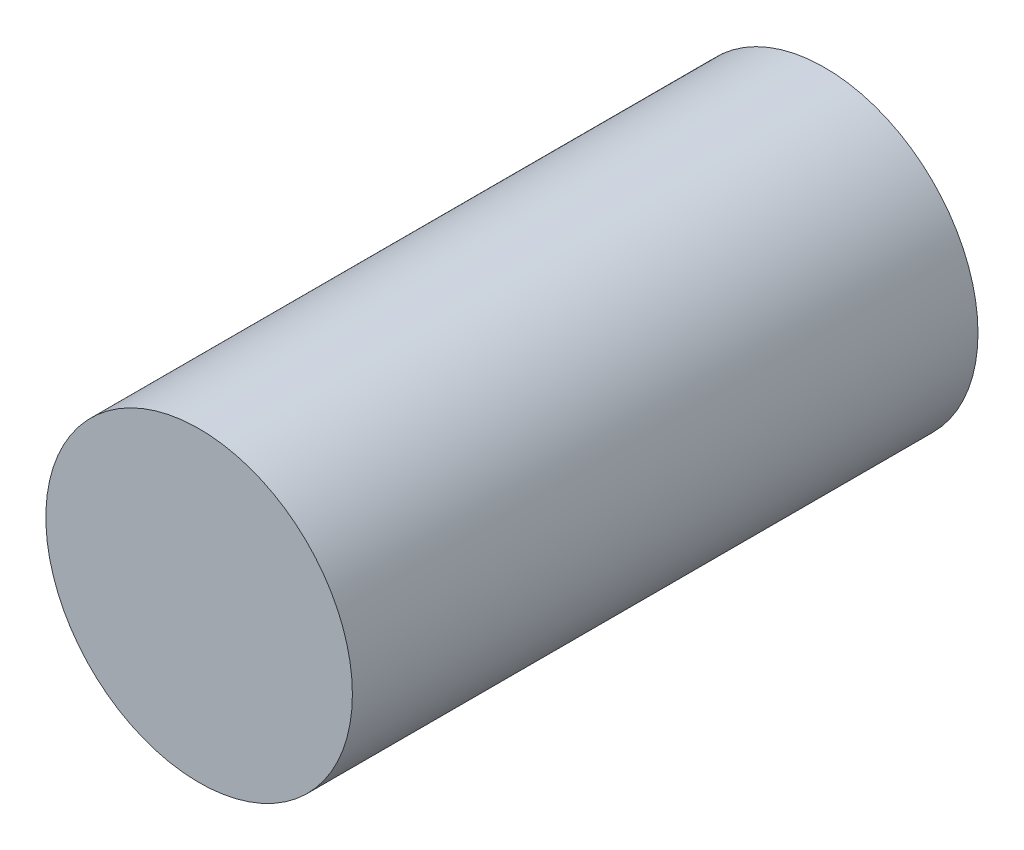
SolidWorks part; units mm, degrees
ref_plane "前视基准面" through (0, 0, 0) normal (0, 0, 1) x (1, 0, 0)
ref_plane "上视基准面" through (0, 0, 0) normal (0, 1, 0) x (1, 0, 0)
ref_plane "右视基准面" through (0, 0, 0) normal (1, 0, 0) x (0, 0, -1)
other "Configuration Table"
sketch "草图1" plane through (0, 0, 0) normal (0, 0, 1) x (1, 0, 0)
  circle A0 centre (0, 0) radius 4.9
  dimension "D1" = 9.8
extrude "凸台-拉伸1" add sketch "草图1" along normal blind 20
